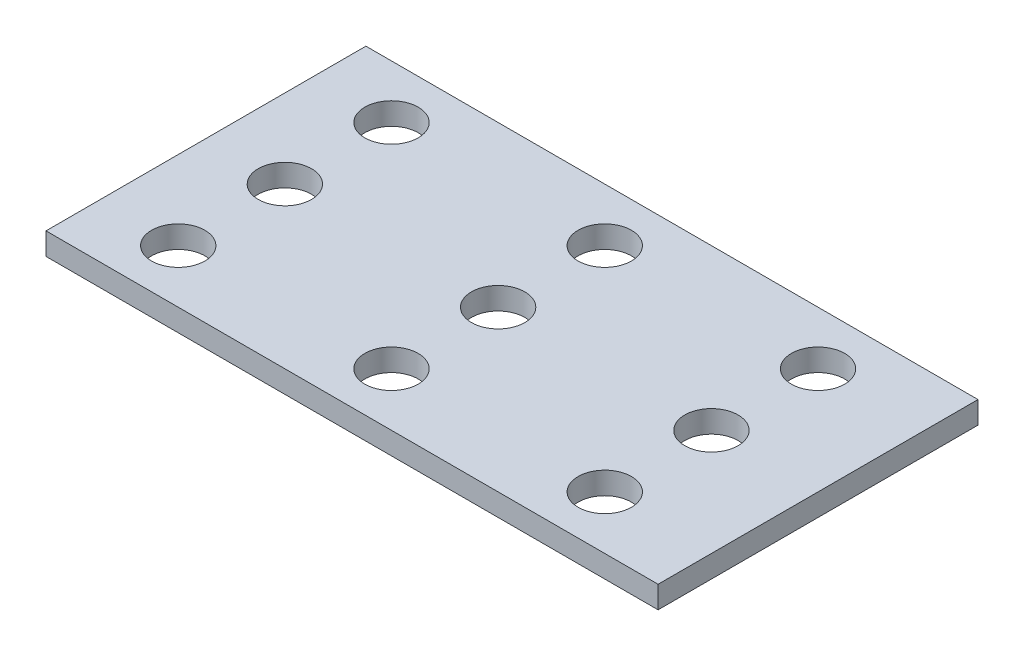
SolidWorks part; units mm, degrees
ref_plane "Front Plane" through (0, 0, 0) normal (0, 0, 1) x (1, 0, 0)
ref_plane "Top Plane" through (0, 0, 0) normal (0, 1, 0) x (1, 0, 0)
ref_plane "Right Plane" through (0, 0, 0) normal (1, 0, 0) x (0, 0, -1)
sketch "Sketch2" plane through (0, 0, 0) normal (0, 1, 0) x (1, 0, 0)
  line L1 (0, 0) -> (-57.4, 0)
  line L2 (0, 0) -> (0, 30)
  line L3 (0, 30) -> (-57.4, 30)
  line L4 (-57.4, 0) -> (-57.4, 30)
  circle A0 centre (-50, 25) radius 2.5
  circle A1 centre (-50, 15) radius 2.5
  circle A2 centre (-50, 5) radius 2.5
  circle A3 centre (-30, 5) radius 2.5
  circle A4 centre (-30, 15) radius 2.5
  circle A5 centre (-30, 25) radius 2.5
  circle A6 centre (-10, 5) radius 2.5
  circle A7 centre (-10, 15) radius 2.5
  circle A8 centre (-10, 25) radius 2.5
  dimension "D3" = 3
  dimension "D1" = 57.4
  dimension "D2" = 30
extrude "Boss-Extrude1" add sketch "Sketch2" along normal mid plane 2.08
